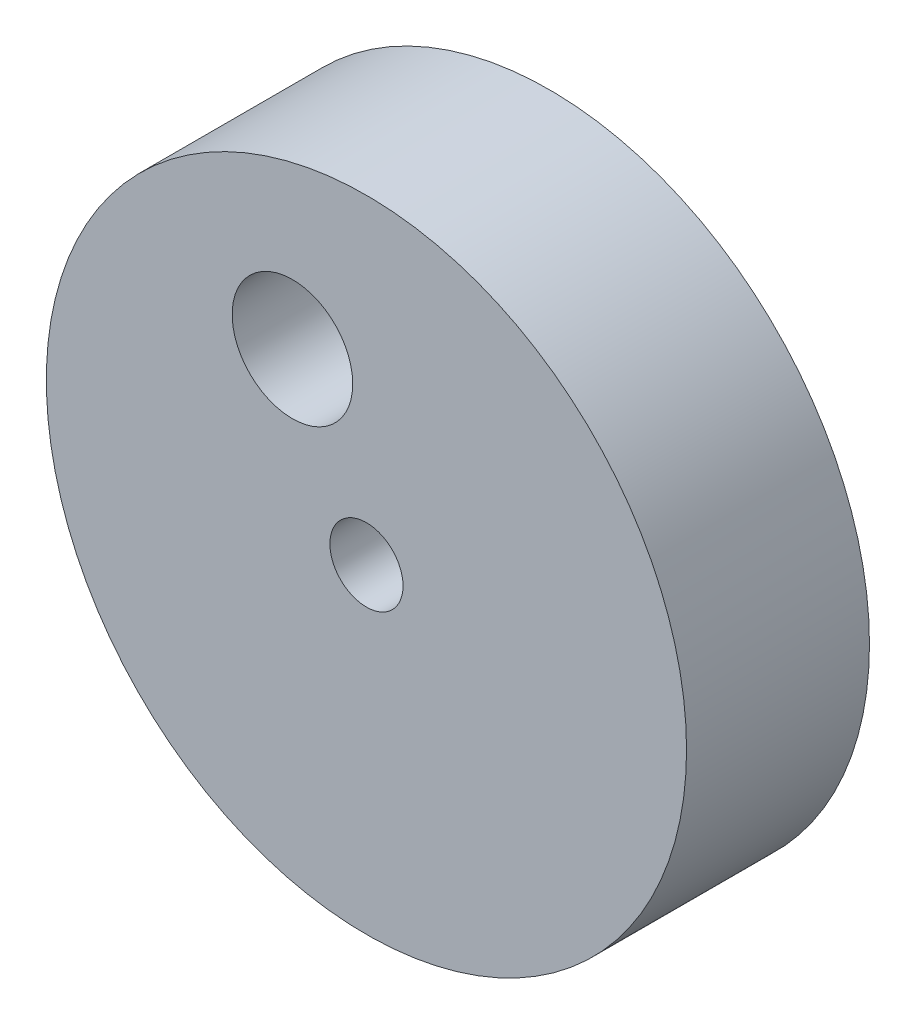
SolidWorks part; units mm, degrees
ref_plane "正面" through (0, 0, 0) normal (0, 0, 1) x (1, 0, 0)
ref_plane "平面" through (0, 0, 0) normal (0, 1, 0) x (1, 0, 0)
ref_plane "右側面" through (0, 0, 0) normal (1, 0, 0) x (0, 0, -1)
sketch "ｽｹｯﾁ1" plane through (0, 0, 0) normal (0, 0, 1) x (1, 0, 0)
  circle A0 centre (0, 0) radius 175
  circle A1 centre (0, 0) radius 20
  circle A2 centre (-40.4643, 81.9156) radius 32.957
extrude "ﾎﾞｽ - 押し出し1" add sketch "ｽｹｯﾁ1" along normal blind 100
